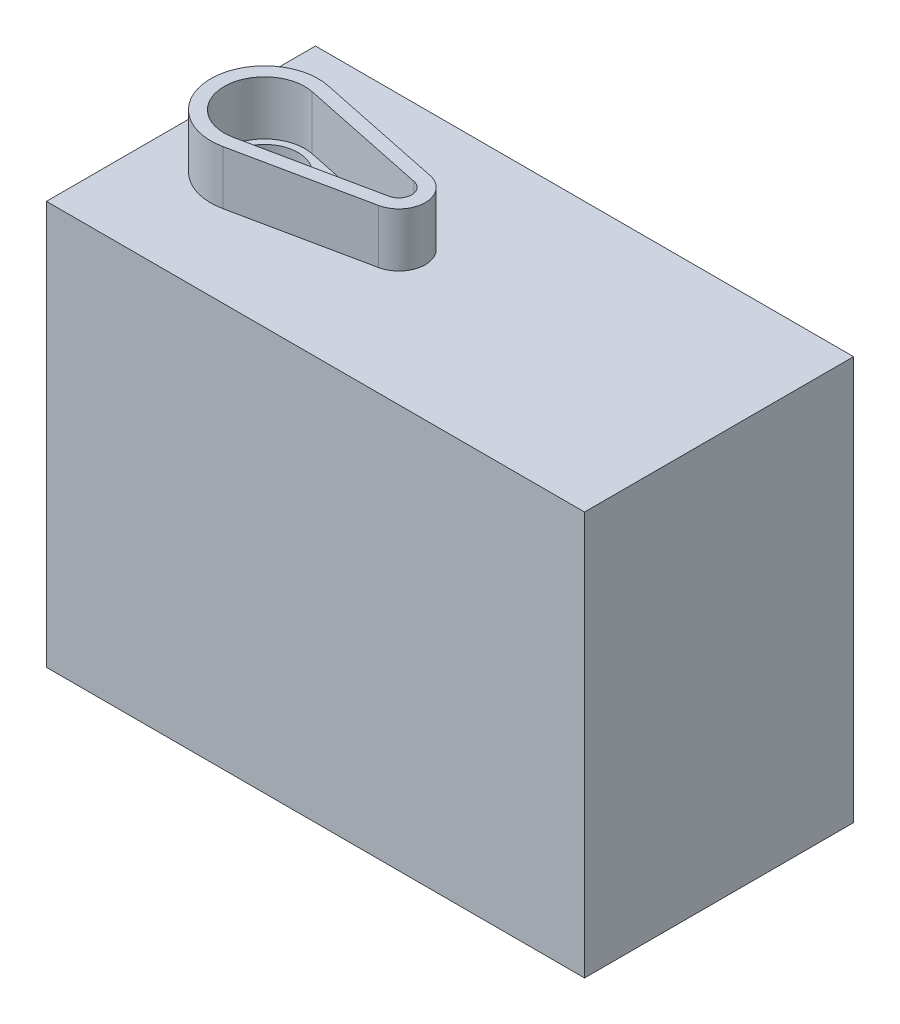
SolidWorks part; units mm, degrees
ref_plane "Front Plane" through (0, 0, 0) normal (0, 0, 1) x (1, 0, 0)
ref_plane "Top Plane" through (0, 0, 0) normal (0, 1, 0) x (1, 0, 0)
ref_plane "Right Plane" through (0, 0, 0) normal (1, 0, 0) x (0, 0, -1)
sketch "Sketch1" plane through (0, 0, 0) normal (0, 0, 1) x (1, 0, 0)
  line L1 (-20, 15) -> (20, 15)
  line L2 (-20, 15) -> (-20, -15)
  line L3 (-20, -15) -> (20, -15)
  line L4 (20, 15) -> (20, -15)
  line L5 (-20, 15) -> (20, -15) construction
  line L6 (-20, -15) -> (20, 15) construction
  point P0 (0, 0)
  dimension "D1" = 40
  dimension "D2" = 30
extrude "Boss-Extrude1" add sketch "Sketch1" against normal blind 20
sketch "Sketch3" plane through (0, 15, 0) normal (0, 1, 0) x (1, 0, 0)
  line L0 (-23.9554, 10) -> (3.0473, 10) construction
  line L1 (-12.9772, 13.9146) -> (-3.4003, 11.9219)
  line L2 (-12.9772, 6.0854) -> (-3.4003, 8.0781)
  line L3 (-13.1809, 12.9356) -> (-3.604, 10.9429)
  line L4 (-13.1809, 7.0644) -> (-3.604, 9.0571)
  arc A0 (-12.9772, 13.9146) -> (-12.9772, 6.0854) centre (-13.7917, 10) ccw
  arc A1 (-3.4003, 8.0781) -> (-3.4003, 11.9219) centre (-3.8002, 10) ccw
  arc A2 (-3.604, 9.0571) -> (-3.604, 10.9429) centre (-3.8002, 10) ccw
  arc A3 (-13.1809, 12.9356) -> (-13.1809, 7.0644) centre (-13.7917, 10) ccw
  dimension "D1" = 10
  dimension "D2" = 1
extrude "Boss-Extrude2" add sketch "Sketch3" along normal blind 4
sketch "Sketch4" plane through (0, 15, 0) normal (0, 1, 0) x (1, 0, 0)
  circle A0 centre (-13.7917, 10) radius 2.5
  dimension "D1" = 5
extrude "Cut-Extrude1" cut sketch "Sketch4" against normal blind 5
